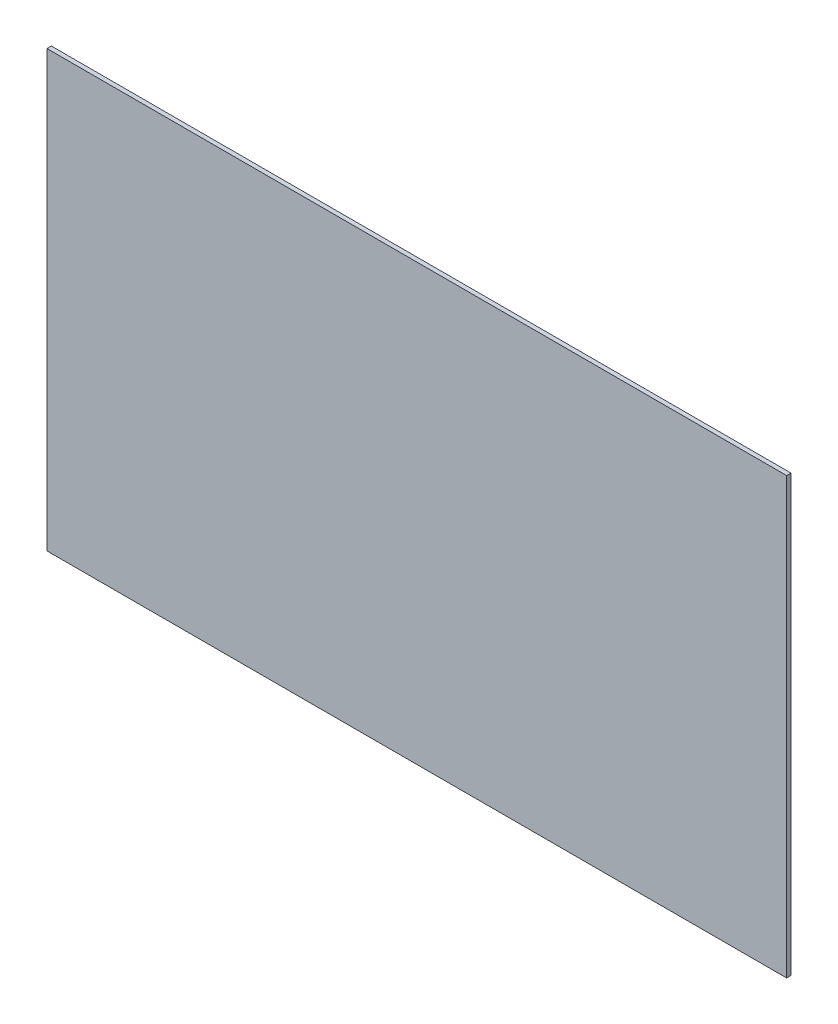
SolidWorks part; units mm, degrees
ref_plane "Plan de face" through (0, 0, 0) normal (0, 0, 1) x (1, 0, 0)
ref_plane "Plan de dessus" through (0, 0, 0) normal (0, 1, 0) x (1, 0, 0)
ref_plane "Plan de droite" through (0, 0, 0) normal (1, 0, 0) x (0, 0, -1)
sketch "Esquisse1" plane through (0, 0, 0) normal (0, 0, 1) x (1, 0, 0)
  line L1 (0, 0) -> (85, 0)
  line L2 (0, 0) -> (0, 50)
  line L3 (0, 50) -> (85, 50)
  line L4 (85, 0) -> (85, 50)
  dimension "D1" = 85
  dimension "D2" = 50
extrude "Boss.-Extru.1" add sketch "Esquisse1" along normal blind 0.5
